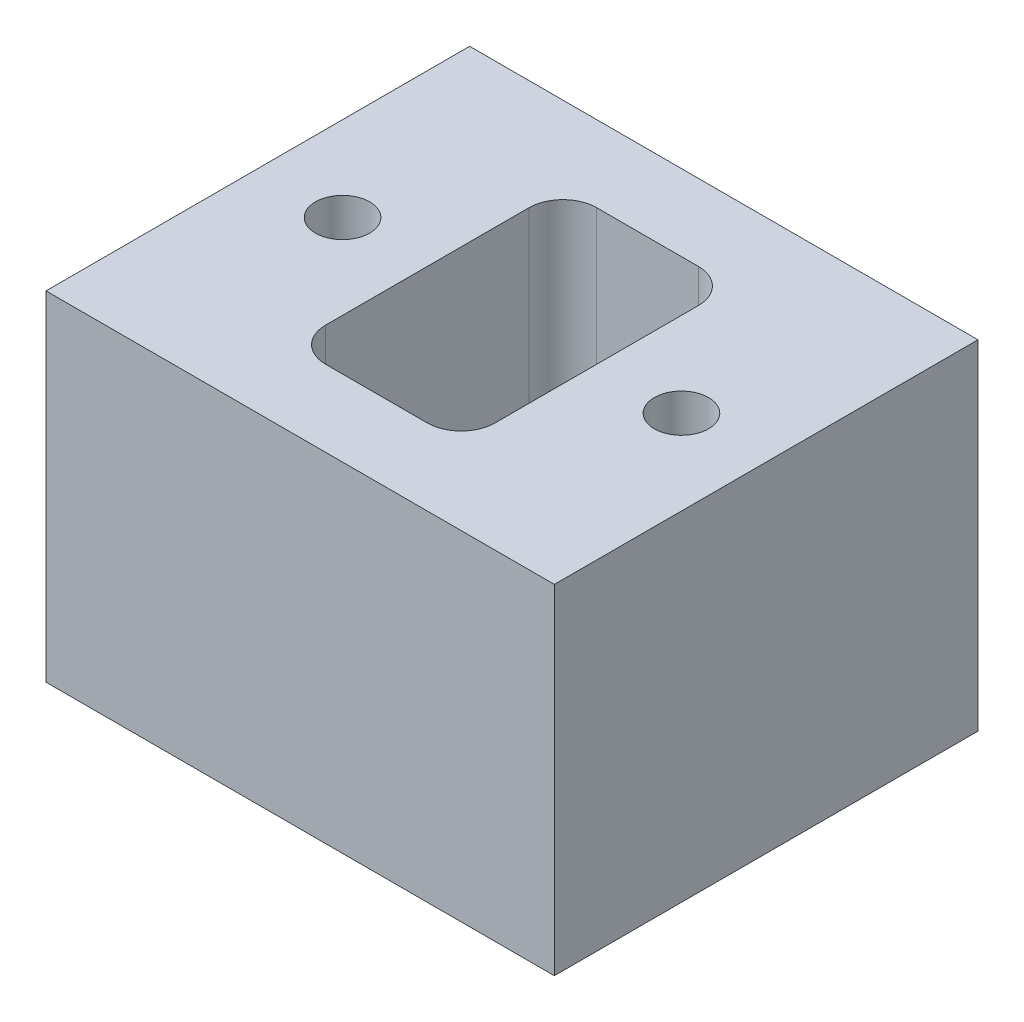
SolidWorks part; units mm, degrees
ref_plane "前视基准面" through (0, 0, 0) normal (0, 0, 1) x (1, 0, 0)
ref_plane "上视基准面" through (0, 0, 0) normal (0, 1, 0) x (1, 0, 0)
ref_plane "右视基准面" through (0, 0, 0) normal (1, 0, 0) x (0, 0, -1)
sketch "草图1" plane through (0, 0, 0) normal (0, 1, 0) x (1, 0, 0)
  line L0 (-15, 0) -> (15, 0) construction
  line L1 (-15, -12.5) -> (15, -12.5)
  line L2 (-15, -12.5) -> (-15, 12.5)
  line L3 (-15, 12.5) -> (15, 12.5)
  line L4 (15, -12.5) -> (15, 12.5)
  line L5 (-15, -12.5) -> (15, 12.5) construction
  line L6 (-15, 12.5) -> (15, -12.5) construction
  circle A0 centre (-10, 0) radius 1.6
  circle A1 centre (10, 0) radius 1.6
  point P0 (0, 0)
  dimension "D3" = 3.2
  dimension "D4" = 3.2
  dimension "D5" = 5
  dimension "D6" = 5
  dimension "D1" = 25
  dimension "D2" = 30
extrude "凸台-拉伸1" add sketch "草图1" along normal blind 20
sketch "草图2" plane through (0, 20, 0) normal (0, 1, 0) x (1, 0, 0)
  line L1 (-3, -8) -> (3, -8)
  line L2 (-5, -6) -> (-5, 6)
  line L3 (-3, 8) -> (3, 8)
  line L4 (5, -6) -> (5, 6)
  line L5 (-5, -8) -> (5, 8) construction
  line L6 (-5, 8) -> (5, -8) construction
  arc A0 (-3, -8) -> (-5, -6) centre (-3, -6) cw
  arc A1 (3, -8) -> (5, -6) centre (3, -6) ccw
  arc A2 (3, 8) -> (5, 6) centre (3, 6) cw
  arc A3 (-5, 6) -> (-3, 8) centre (-3, 6) cw
  point P0 (0, 0)
  dimension "D3" = 2
  dimension "D1" = 16
  dimension "D2" = 10
extrude "切除-拉伸1" cut sketch "草图2" against normal blind 20
